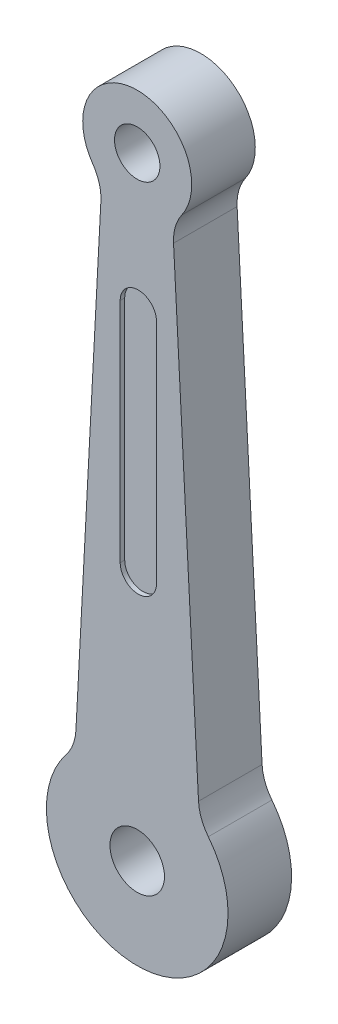
SolidWorks part; units mm, degrees
ref_plane "前视" through (0, 0, 0) normal (0, 0, 1) x (1, 0, 0)
ref_plane "上视" through (0, 0, 0) normal (0, 1, 0) x (1, 0, 0)
ref_plane "右视" through (0, 0, 0) normal (1, 0, 0) x (0, 0, -1)
sketch "草图1" plane through (0, 0, 0) normal (0, 0, 1) x (1, 0, 0)
  line L0 (-8, 121.8011) -> (-13.5, 18.1359)
  line L1 (0, 135) -> (0, 0) construction
  line L2 (8, 121.8011) -> (13.5, 18.1359)
  circle A0 centre (0, 0) radius 6
  arc A1 (-15.6573, 12.4438) -> (15.6573, 12.4438) centre (0, 0) ccw
  circle A2 centre (0, 135) radius 5
  arc A3 (9.8105, 128.0896) -> (-9.8105, 128.0896) centre (0, 135) ccw
  arc A4 (-8, 121.8011) -> (-9.8105, 128.0896) centre (-17.986, 122.3309) ccw
  arc A5 (-15.6573, 12.4438) -> (-13.5, 18.1359) centre (-23.486, 18.6657) ccw
  arc A6 (15.6573, 12.4438) -> (13.5, 18.1359) centre (23.486, 18.6657) cw
  arc A7 (8, 121.8011) -> (9.8105, 128.0896) centre (17.986, 122.3309) cw
  dimension "D1" = 20
  dimension "D2" = 12
  dimension "D3" = 12
  dimension "D4" = 10
  dimension "D5" = 10
  dimension "D6" = 16
  dimension "D7" = 27
  dimension "D8" = 135
extrude "拉伸1" add sketch "草图1" against normal blind 14
sketch "草图2" plane through (0, 0, 0) normal (0, 0, 1) x (1, 0, 0)
  line L2 (-3.7519, 105) -> (-3.7519, 55)
  line L4 (4.2481, 105) -> (4.2481, 55)
  arc A0 (4.2481, 105) -> (-3.7519, 105) centre (0.2481, 105) ccw
  arc A1 (-3.7519, 55) -> (4.2481, 55) centre (0.2481, 55) ccw
  circle A2 centre (0, 135) radius 5 construction
  dimension "D3" = 30
  dimension "D4" = 4
  dimension "D5" = 4
  dimension "D1" = 8
  dimension "D2" = 50
extrude "切除-拉伸1" cut sketch "草图2" against normal blind 1
sketch "草图3" plane through (0, 0, -14) normal (0, 0, -1) x (-1, 0, 0)
  line L2 (3.7519, 55) -> (3.7519, 105)
  line L3 (-4.2481, 105) -> (-4.2481, 55)
  line L4 (3.7519, 55) -> (3.7519, 105)
  line L5 (-4.2481, 105) -> (-4.2481, 55)
  arc A2 (3.7519, 105) -> (-4.2481, 105) centre (-0.2481, 105) ccw
  arc A3 (-4.2481, 55) -> (3.7519, 55) centre (-0.2481, 55) ccw
  arc A4 (3.7519, 105) -> (-4.2481, 105) centre (-0.2481, 105) ccw
  arc A5 (-4.2481, 55) -> (3.7519, 55) centre (-0.2481, 55) ccw
  dimension "D1" = 0
extrude "切除-拉伸2" cut sketch "草图3" against normal blind 1
